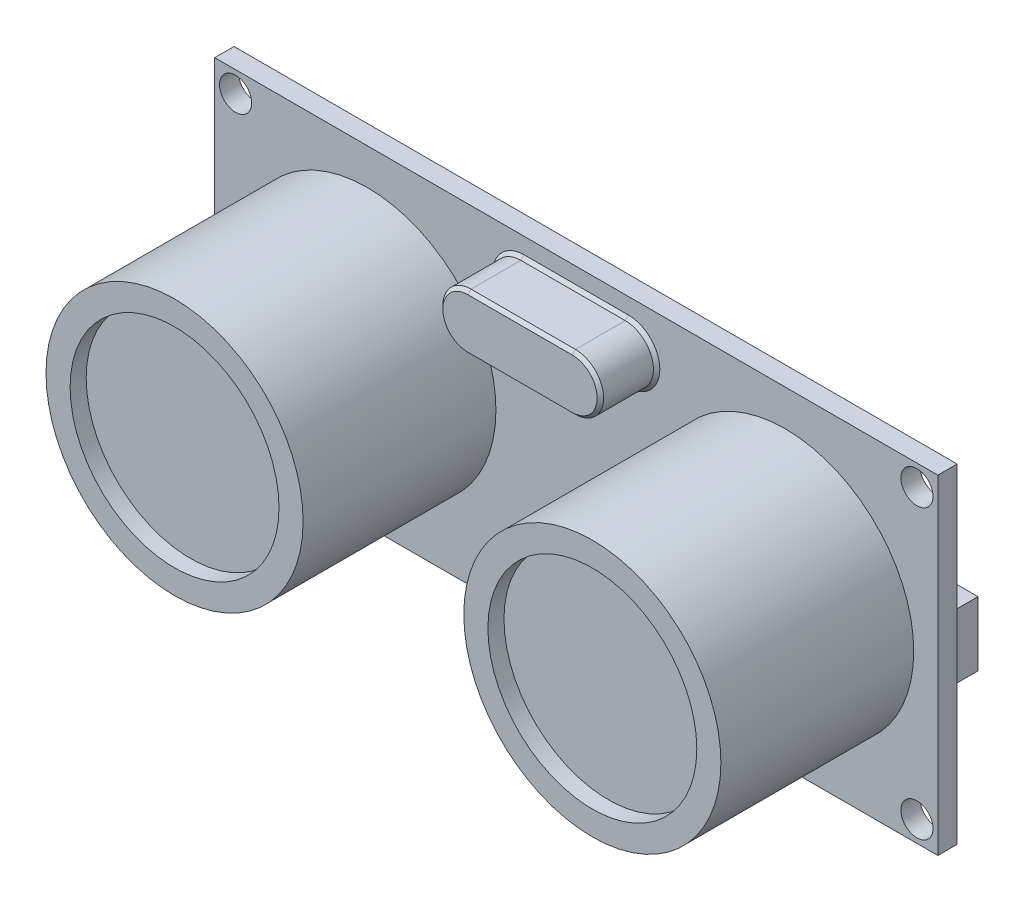
SolidWorks part; units mm, degrees
ref_plane "Front Plane" through (0, 0, 0) normal (0, 0, 1) x (1, 0, 0)
ref_plane "Top Plane" through (0, 0, 0) normal (0, 1, 0) x (1, 0, 0)
ref_plane "Right Plane" through (0, 0, 0) normal (1, 0, 0) x (0, 0, -1)
sketch "Sketch1" plane through (0, 0, 0) normal (0, 0, 1) x (1, 0, 0)
  line L0 (-1000, 0) -> (49000, 0) construction
  line L1 (-22.5, -10.25) -> (22.5, -10.25)
  line L2 (-22.5, -10.25) -> (-22.5, 10.25)
  line L3 (-22.5, 10.25) -> (22.5, 10.25)
  line L4 (22.5, -10.25) -> (22.5, 10.25)
  line L5 (0, -1000) -> (0, 49000) construction
  circle A0 centre (21.2, 8.95) radius 1
  circle A1 centre (21.2, -8.95) radius 1
  circle A2 centre (-21.2, -8.95) radius 1
  circle A3 centre (-21.2, 8.95) radius 1
  dimension "D5" = 2
  dimension "D1" = 45
  dimension "D2" = 22.5
  dimension "D3" = 20.5
  dimension "D4" = 10.25
  dimension "D6" = 1.3
  dimension "D7" = 1.3
extrude "Boss-Extrude1" add sketch "Sketch1" along normal blind 1.2
sketch "Sketch2" plane through (0, 0, 1.2) normal (0, 0, 1) x (1, 0, 0)
  line L0 (-3.25, 7.3) -> (3.25, 7.3) construction
  line L1 (-3.25, 9.05) -> (3.25, 9.05)
  line L2 (-3.25, 5.55) -> (3.25, 5.55)
  line L3 (22.5, 10.25) -> (-22.5, 10.25) construction
  arc A0 (-3.25, 9.05) -> (-3.25, 5.55) centre (-3.25, 7.3) ccw
  arc A1 (3.25, 5.55) -> (3.25, 9.05) centre (3.25, 7.3) ccw
  point P2 (0, 7.3)
  point P7 (0, 9.05)
  point P10 (0, 0)
  dimension "D1" = 10
  dimension "D2" = 3.5
  dimension "D3" = 1.2
extrude "Boss-Extrude2" add sketch "Sketch2" along normal blind 3.5
chamfer "Chamfer1" distance 0.2 angle 45 8 edges at (0, 9.05, 4.7) (5, 7.3, 4.7) (0, 5.55, 4.7) (-5, 7.3, 4.7) (5, 7.3, 1.2) (0, 9.05, 1.2) (0, 5.55, 1.2) (-5, 7.3, 1.2)
sketch "Sketch3" plane through (0, 0, 0) normal (0, 0, -1) x (-1, 0, 0)
  line L0 (22.5, -10.25) -> (-22.5, -10.25) construction
  line L1 (-4.8, -10.15) -> (-2.7, -10.15)
  line L2 (-5, -9.95) -> (-5, -7.85)
  line L3 (-4.8, -7.65) -> (-2.7, -7.65)
  line L4 (-2.5, -9.95) -> (-2.5, -7.85)
  line L5 (-2.5, -9.95) -> (-2.5, -7.85)
  line L6 (-2.3, -10.15) -> (-0.2, -10.15)
  line L7 (0, -9.95) -> (0, -7.85)
  line L8 (-2.3, -7.65) -> (-0.2, -7.65)
  line L9 (0, -9.95) -> (0, -7.85)
  line L10 (0.2, -10.15) -> (2.3, -10.15)
  line L11 (2.5, -9.95) -> (2.5, -7.85)
  line L12 (0.2, -7.65) -> (2.3, -7.65)
  line L13 (2.5, -9.95) -> (2.5, -7.85)
  line L14 (2.7, -10.15) -> (4.8, -10.15)
  line L15 (5, -9.95) -> (5, -7.85)
  line L16 (2.7, -7.65) -> (4.8, -7.65)
  arc A0 (-4.8, -10.15) -> (-5, -9.95) centre (-4.8, -9.95) cw
  arc A1 (-2.7, -10.15) -> (-2.5, -9.95) centre (-2.7, -9.95) ccw
  arc A2 (-2.7, -7.65) -> (-2.5, -7.85) centre (-2.7, -7.85) cw
  arc A3 (-5, -7.85) -> (-4.8, -7.65) centre (-4.8, -7.85) cw
  arc A4 (-2.5, -7.85) -> (-2.3, -7.65) centre (-2.3, -7.85) cw
  arc A5 (-2.3, -10.15) -> (-2.5, -9.95) centre (-2.3, -9.95) cw
  arc A6 (-0.2, -10.15) -> (0, -9.95) centre (-0.2, -9.95) ccw
  arc A7 (-0.2, -7.65) -> (0, -7.85) centre (-0.2, -7.85) cw
  arc A8 (0, -7.85) -> (0.2, -7.65) centre (0.2, -7.85) cw
  arc A9 (0.2, -10.15) -> (0, -9.95) centre (0.2, -9.95) cw
  arc A10 (2.3, -10.15) -> (2.5, -9.95) centre (2.3, -9.95) ccw
  arc A11 (2.3, -7.65) -> (2.5, -7.85) centre (2.3, -7.85) cw
  arc A12 (2.5, -7.85) -> (2.7, -7.65) centre (2.7, -7.85) cw
  arc A13 (2.7, -10.15) -> (2.5, -9.95) centre (2.7, -9.95) cw
  arc A14 (4.8, -10.15) -> (5, -9.95) centre (4.8, -9.95) ccw
  arc A15 (4.8, -7.65) -> (5, -7.85) centre (4.8, -7.85) cw
  point P8 (-5, -10.15)
  point P11 (-2.5, -10.15)
  point P16 (-5, -7.65)
  dimension "D4" = 0.2
  dimension "D1" = 2.5
  dimension "D2" = 2.5
  dimension "D3" = 0.1
  dimension "D6" = 5
  dimension "D7" = 5
  dimension "D5" = 4
extrude "Boss-Extrude3" add sketch "Sketch3" along normal blind 2.5 contours A3 L2 A0 L1 A1 L4 A2 L3 | A7 L8 A4 L4 A5 L6 A6 L7 | A11 L12 A8 L7 A9 L10 A10 L11 | A15 L16 A12 L11 A13 L14 A14 L15
sketch "Sketch4" plane through (-22.5, 0, 0) normal (-1, 0, 0) x (0, 0, 1)
  line L0 (-2.5, -8.9) -> (-3.75, -8.9)
  line L1 (-2.5, -9.95) -> (-2.5, -7.85) construction
  line L2 (-4.5, -9.65) -> (-4.5, -16.4)
  line L3 (-2.5, -8.9) -> (2.2, -8.9)
  line L4 (1.2, -10.25) -> (1.2, 10.25) construction
  arc A0 (-3.75, -8.9) -> (-4.5, -9.65) centre (-3.75, -9.65) ccw
  point P7 (-4.5, -8.9)
  dimension "D3" = 0.75
  dimension "D1" = 2
  dimension "D2" = 7.5
  dimension "D4" = 1
sketch "Sketch5" plane through (0, 0, -2.5) normal (0, 0, -1) x (-1, 0, 0)
  line L0 (-5, -9.95) -> (-5, -7.85) construction
  line L1 (-4, -9.15) -> (-3.5, -9.15)
  line L2 (-4, -9.15) -> (-4, -8.65)
  line L3 (-4, -8.65) -> (-3.5, -8.65)
  line L4 (-3.5, -9.15) -> (-3.5, -8.65)
  line L5 (-4.8, -7.65) -> (-2.7, -7.65) construction
  line L6 (-1.5, -9.15) -> (-1.5, -8.65)
  line L7 (-1.5, -9.15) -> (-1, -9.15)
  line L8 (-1, -9.15) -> (-1, -8.65)
  line L9 (-1.5, -8.65) -> (-1, -8.65)
  line L10 (1, -9.15) -> (1, -8.65)
  line L11 (1, -9.15) -> (1.5, -9.15)
  line L12 (1.5, -9.15) -> (1.5, -8.65)
  line L13 (1, -8.65) -> (1.5, -8.65)
  line L14 (3.5, -9.15) -> (3.5, -8.65)
  line L15 (3.5, -9.15) -> (4, -9.15)
  line L16 (4, -9.15) -> (4, -8.65)
  line L17 (3.5, -8.65) -> (4, -8.65)
  dimension "D1" = 0.5
  dimension "D2" = 0.5
  dimension "D3" = 1
  dimension "D4" = 1
  dimension "D6" = 4
  dimension "D5" = 4
sweep "Sweep1" add profiles "Sketch5" path "Sketch4"
sketch "Sketch6" plane through (0, 0, 1.2) normal (0, 0, 1) x (1, 0, 0)
  line L0 (-13, 0) -> (13, 0)
  circle A0 centre (-13, 0) radius 8
  circle A1 centre (13, 0) radius 8
  dimension "D3" = 16
  dimension "D4" = 16
  dimension "D1" = 26
  dimension "D2" = 13
extrude "Boss-Extrude4" add sketch "Sketch6" along normal blind 12
sketch "Sketch7" plane through (0, 0, 13.2) normal (0, 0, 1) x (1, 0, 0)
  circle A0 centre (13, 0) radius 8 construction
  circle A1 centre (-13, 0) radius 8 construction
  circle A2 centre (13, 0) radius 8 construction
  circle A3 centre (-13, 0) radius 8 construction
  circle A4 centre (-13, 0) radius 6.5
  circle A5 centre (13, 0) radius 6.5
  dimension "D1" = 1.5
extrude "Cut-Extrude1" cut sketch "Sketch7" against normal blind 1
sketch "Sketch8" plane through (0, 0, 1.2) normal (0, 0, 1) x (1, 0, 0)
  line L0 (-22.5, -10.25) -> (22.5, -10.25) construction
  line L1 (-4, -9.15) -> (-3.5, -9.15)
  line L2 (-4, -9.15) -> (-4, -8.65)
  line L3 (-4, -8.65) -> (-3.5, -8.65)
  line L4 (-3.5, -9.15) -> (-3.5, -8.65)
  line L5 (-4, -9.65) -> (-4, -16.4) construction
  line L6 (-1.5, -9.15) -> (-1.5, -8.65)
  line L7 (-1.5, -9.15) -> (-1, -9.15)
  line L8 (-1, -9.15) -> (-1, -8.65)
  line L9 (-1.5, -8.65) -> (-1, -8.65)
  line L10 (1, -9.15) -> (1, -8.65)
  line L11 (1, -9.15) -> (1.5, -9.15)
  line L12 (1.5, -9.15) -> (1.5, -8.65)
  line L13 (1, -8.65) -> (1.5, -8.65)
  line L14 (3.5, -9.15) -> (3.5, -8.65)
  line L15 (3.5, -9.15) -> (4, -9.15)
  line L16 (4, -9.15) -> (4, -8.65)
  line L17 (3.5, -8.65) -> (4, -8.65)
  dimension "D1" = 0.5
  dimension "D2" = 0.5
  dimension "D3" = 1.1
  dimension "D5" = 4
  dimension "D4" = 4
extrude "Boss-Extrude5" add sketch "Sketch8" along normal blind 1
sketch "Sketch9" plane through (0, 0, 0) normal (0, 0, -1) x (-1, 0, 0)
  line L0 (-22.5, -10.25) -> (-22.5, 10.25) construction
  line L1 (-22.3, -1.75) -> (-13.8, -1.75)
  line L2 (-22.3, -1.75) -> (-22.3, 2.25)
  line L3 (-22.3, 2.25) -> (-13.8, 2.25)
  line L4 (-13.8, -1.75) -> (-13.8, 2.25)
  line L5 (-4.25, -2.25) -> (4.25, -2.25)
  line L6 (-4.25, -2.25) -> (-4.25, 1.75)
  line L7 (-4.25, 1.75) -> (4.25, 1.75)
  line L8 (4.25, -2.25) -> (4.25, 1.75)
  line L9 (16.5, -5.25) -> (20.5, -5.25)
  line L10 (16.5, -5.25) -> (16.5, 4.75)
  line L11 (16.5, 4.75) -> (20.5, 4.75)
  line L12 (20.5, -5.25) -> (20.5, 4.75)
  line L13 (22.5, 10.25) -> (22.5, -10.25) construction
  line L14 (-22.5, 10.25) -> (22.5, 10.25) construction
  line L15 (22.5, -10.25) -> (-22.5, -10.25) construction
  point P20 (-4.25, -0.25)
  dimension "D1" = 8.5
  dimension "D2" = 8.5
  dimension "D3" = 10
  dimension "D4" = 4
  dimension "D5" = 4
  dimension "D6" = 4
  dimension "D7" = 0.2
  dimension "D8" = 2
  dimension "D9" = 8.5
  dimension "D10" = 8.5
  dimension "D11" = 4.25
  dimension "D12" = 5
extrude "Boss-Extrude6" add sketch "Sketch9" along normal blind 1.5
sketch "Sketch10" plane through (0, 0, 0) normal (0, 0, -1) x (-1, 0, 0)
  line L0 (-13.8, 2.25) -> (-22.3, 2.25) construction
  line L1 (-21.55, 2.25) -> (-14.55, 2.25)
  line L2 (-21.55, 2.25) -> (-21.55, 3.25)
  line L3 (-21.55, 3.25) -> (-14.55, 3.25)
  line L4 (-14.55, 2.25) -> (-14.55, 3.25)
  line L5 (-22.3, -1.75) -> (-13.8, -1.75) construction
  line L6 (-21.55, -1.75) -> (-14.55, -1.75)
  line L7 (-21.55, -1.75) -> (-21.55, -2.75)
  line L8 (-21.55, -2.75) -> (-14.55, -2.75)
  line L9 (-14.55, -1.75) -> (-14.55, -2.75)
  line L10 (4.25, 1.75) -> (-4.25, 1.75) construction
  line L11 (-3.5, 1.75) -> (3.5, 1.75)
  line L12 (-3.5, 1.75) -> (-3.5, 2.75)
  line L13 (-3.5, 2.75) -> (3.5, 2.75)
  line L14 (3.5, 1.75) -> (3.5, 2.75)
  line L15 (-4.25, -2.25) -> (4.25, -2.25) construction
  line L16 (-3.5, -2.25) -> (3.5, -2.25)
  line L17 (-3.5, -2.25) -> (-3.5, -3.25)
  line L18 (-3.5, -3.25) -> (3.5, -3.25)
  line L19 (3.5, -2.25) -> (3.5, -3.25)
  line L20 (16.5, 4.75) -> (16.5, -5.25) construction
  line L21 (16.5, -4) -> (15.5, -4)
  line L22 (16.5, -4) -> (16.5, 3.5)
  line L23 (16.5, 3.5) -> (15.5, 3.5)
  line L24 (15.5, -4) -> (15.5, 3.5)
  line L25 (20.5, -5.25) -> (20.5, 4.75) construction
  line L26 (20.5, -4) -> (21.5, -4)
  line L27 (20.5, -4) -> (20.5, 3.5)
  line L28 (20.5, 3.5) -> (21.5, 3.5)
  line L29 (21.5, -4) -> (21.5, 3.5)
  line L30 (20.5, 4.75) -> (16.5, 4.75) construction
  line L31 (-4.25, 1.75) -> (-4.25, -2.25) construction
  line L32 (-13.8, -1.75) -> (-13.8, 2.25) construction
  line L33 (-8.8, 3.0357) -> (-8.8, 3.7857)
  line L34 (-8.8, 4.5) -> (-7.3, 4.5)
  line L35 (-8.8, 4.5) -> (-8.8, 5.25)
  line L36 (-8.8, 5.25) -> (-7.3, 5.25)
  line L37 (-7.3, 4.5) -> (-7.3, 5.25)
  line L38 (-8.8, 3.0357) -> (-7.3, 3.0357)
  line L39 (-7.3, 3.0357) -> (-7.3, 3.7857)
  line L40 (-8.8, 3.7857) -> (-7.3, 3.7857)
  line L41 (-8.8, 1.5714) -> (-8.8, 2.3214)
  line L42 (-8.8, 1.5714) -> (-7.3, 1.5714)
  line L43 (-7.3, 1.5714) -> (-7.3, 2.3214)
  line L44 (-8.8, 2.3214) -> (-7.3, 2.3214)
  line L45 (-8.8, 0.1071) -> (-8.8, 0.8571)
  line L46 (-8.8, 0.1071) -> (-7.3, 0.1071)
  line L47 (-7.3, 0.1071) -> (-7.3, 0.8571)
  line L48 (-8.8, 0.8571) -> (-7.3, 0.8571)
  line L49 (-8.8, -1.3571) -> (-8.8, -0.6071)
  line L50 (-8.8, -1.3571) -> (-7.3, -1.3571)
  line L51 (-7.3, -1.3571) -> (-7.3, -0.6071)
  line L52 (-8.8, -0.6071) -> (-7.3, -0.6071)
  line L53 (-8.8, -2.8214) -> (-8.8, -2.0714)
  line L54 (-8.8, -2.8214) -> (-7.3, -2.8214)
  line L55 (-7.3, -2.8214) -> (-7.3, -2.0714)
  line L56 (-8.8, -2.0714) -> (-7.3, -2.0714)
  line L57 (-8.8, -4.2857) -> (-8.8, -3.5357)
  line L58 (-8.8, -4.2857) -> (-7.3, -4.2857)
  line L59 (-7.3, -4.2857) -> (-7.3, -3.5357)
  line L60 (-8.8, -3.5357) -> (-7.3, -3.5357)
  line L61 (-8.8, -5.75) -> (-8.8, -5)
  line L62 (-8.8, -5.75) -> (-7.3, -5.75)
  line L63 (-7.3, -5.75) -> (-7.3, -5)
  line L64 (-8.8, -5) -> (-7.3, -5)
  line L65 (-22.5, 10.25) -> (22.5, 10.25) construction
  line L66 (22.5, -10.25) -> (-22.5, -10.25) construction
  point P46 (-8.8, 4.875)
  dimension "D1" = 1
  dimension "D2" = 1
  dimension "D3" = 1
  dimension "D4" = 1
  dimension "D5" = 1
  dimension "D6" = 1
  dimension "D7" = 7.5
  dimension "D8" = 1.25
  dimension "D9" = 7
  dimension "D10" = 0.75
  dimension "D11" = 7.5
  dimension "D12" = 1.25
  dimension "D13" = 7
  dimension "D14" = 0.75
  dimension "D15" = 7
  dimension "D16" = 7
  dimension "D17" = 0.75
  dimension "D18" = 0.75
  dimension "D19" = 1.5
  dimension "D20" = 0.75
  dimension "D21" = 5
  dimension "D23" = 5
  dimension "D24" = 4.5
  dimension "D22" = 8
extrude "Boss-Extrude7" add sketch "Sketch10" along normal blind 0.5
